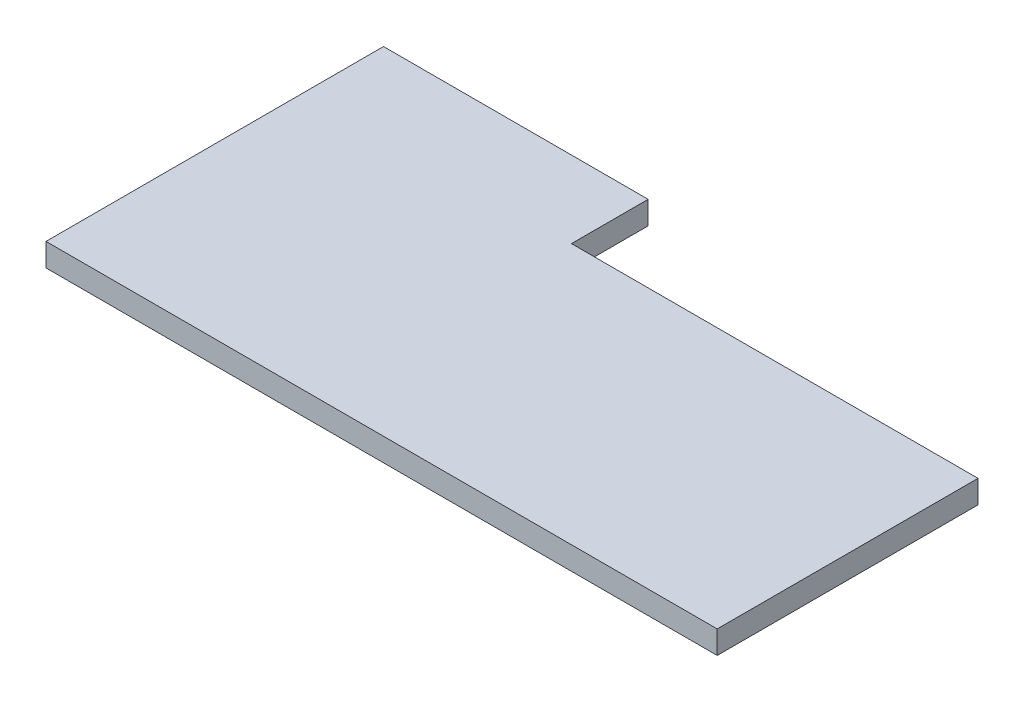
SolidWorks part; units mm, degrees
material "Pine"
ref_plane "Front Plane" through (0, 0, 0) normal (0, 0, 1) x (1, 0, 0)
ref_plane "Top Plane" through (0, 0, 0) normal (0, 1, 0) x (1, 0, 0)
ref_plane "Right Plane" through (0, 0, 0) normal (1, 0, 0) x (0, 0, -1)
sketch "Sketch1" plane through (0, 0, 0) normal (0, 1, 0) x (1, 0, 0)
  line L0 (0, 0) -> (175, 0)
  line L2 (0, 0) -> (0, 88)
  line L3 (0, 88) -> (69, 88)
  line L4 (69, 68) -> (69, 88)
  line L7 (69, 68) -> (175, 68)
  line L8 (175, 0) -> (175, 68)
  dimension "D1" = 69
  dimension "D2" = 88
  dimension "D3" = 175
  dimension "D4" = 20
extrude "Boss-Extrude1" add sketch "Sketch1" along normal blind 6
equation "\"BoardThickness\"= 6"
equation "\"D2@Sketch1\"=100 - \"BoardThickness\"* 2"
equation "\"D1@Boss-Extrude1\"=\"BoardThickness\""
equation "\"D1@Sketch1\"=75-\"BoardThickness\""
